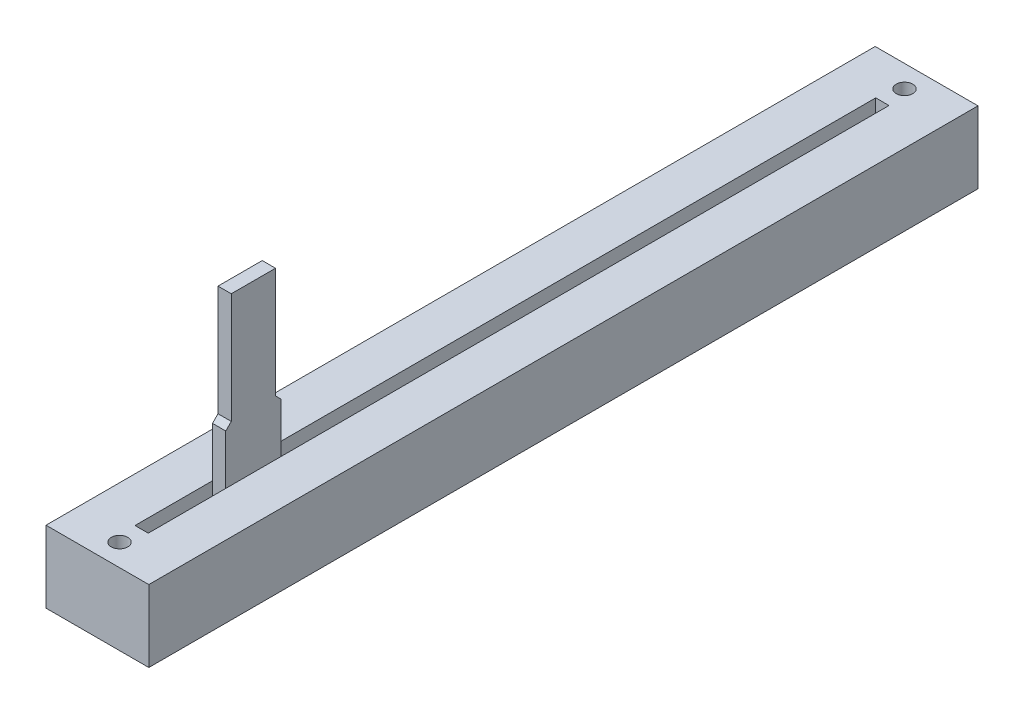
SolidWorks part; units mm, degrees
ref_plane "Plan de face" through (0, 0, 0) normal (0, 0, 1) x (1, 0, 0)
ref_plane "Plan de dessus" through (0, 0, 0) normal (0, 1, 0) x (1, 0, 0)
ref_plane "Plan de droite" through (0, 0, 0) normal (1, 0, 0) x (0, 0, -1)
sketch "Esquisse1" plane through (0, 0, 0) normal (0, 1, 0) x (1, 0, 0)
  line L0 (4.65, 37.5) -> (-4.65, -37.5) construction
  line L1 (-4.65, -37.5) -> (4.65, -37.5)
  line L2 (-4.65, -37.5) -> (-4.65, 37.5)
  line L3 (-4.65, 37.5) -> (4.65, 37.5)
  line L4 (4.65, -37.5) -> (4.65, 37.5)
  point P4 (0, 0)
  dimension "D1" = 75
  dimension "D2" = 9.3
extrude "Boss.-Extru.1" add sketch "Esquisse1" along normal blind 6.5
sketch "Esquisse2" plane through (0, 6.5, 0) normal (0, 1, 0) x (1, 0, 0)
  line L0 (0, 35.5) -> (0, -35.5) construction
  circle A0 centre (0, 35.5) radius 0.75
  circle A1 centre (0, -35.5) radius 0.75
  point P4 (0, 0)
  point P5 (0, 0)
  dimension "D1" = 1.5
  dimension "D2" = 71
extrude "Enlèv. mat.-Extru.1" cut sketch "Esquisse2" against normal blind 4
sketch "Esquisse3" plane through (0, 6.5, 0) normal (0, 1, 0) x (1, 0, 0)
  line L0 (-0.6, 33.5) -> (0.6, -33.5) construction
  line L1 (-0.6, 33.5) -> (0.6, 33.5)
  line L2 (-0.6, 33.5) -> (-0.6, -33.5)
  line L3 (-0.6, -33.5) -> (0.6, -33.5)
  line L4 (0.6, 33.5) -> (0.6, -33.5)
  point P4 (0, 0)
  point P5 (0, 0)
  point P7 (0, 0)
  dimension "D1" = 67
  dimension "D2" = 1.2
extrude "Enlèv. mat.-Extru.2" cut sketch "Esquisse3" against normal blind 4
sketch "Esquisse4" plane through (0, 0, 0) normal (1, 0, 0) x (0, 0, -1)
  line L0 (-26.4916, 2.5) -> (-21.4916, 2.5)
  line L1 (-21.4916, 2.5) -> (-21.4916, 11)
  line L2 (-21.4916, 11) -> (-21.9916, 11.5)
  line L3 (-21.9916, 11.5) -> (-21.9916, 21.5)
  line L4 (-21.9916, 21.5) -> (-25.9916, 21.5)
  line L5 (-25.9916, 21.5) -> (-25.9916, 11.5)
  line L6 (-25.9916, 11.5) -> (-26.4916, 11)
  line L7 (-26.4916, 11) -> (-26.4916, 2.5)
  line L8 (-37.5, 6.5) -> (37.5, 6.5) construction
  line L9 (33.5, 2.5) -> (-33.5, 2.5) construction
  point P2 (0, 0)
  point P9 (-17.9628, 9.8253)
  point P10 (0, 0)
  point P11 (-22.004, 9.5439)
  point P12 (-18.0395, 17.3194)
  point P17 (8.8725, 2.5)
  point P18 (-26.4916, 2.5)
  dimension "D1" = 135
  dimension "D2" = 4
  dimension "D3" = 5
  dimension "D4" = 10
  dimension "D5" = 15
extrude "Boss.-Extru.2" add sketch "Esquisse4" along normal mid plane 1.2
